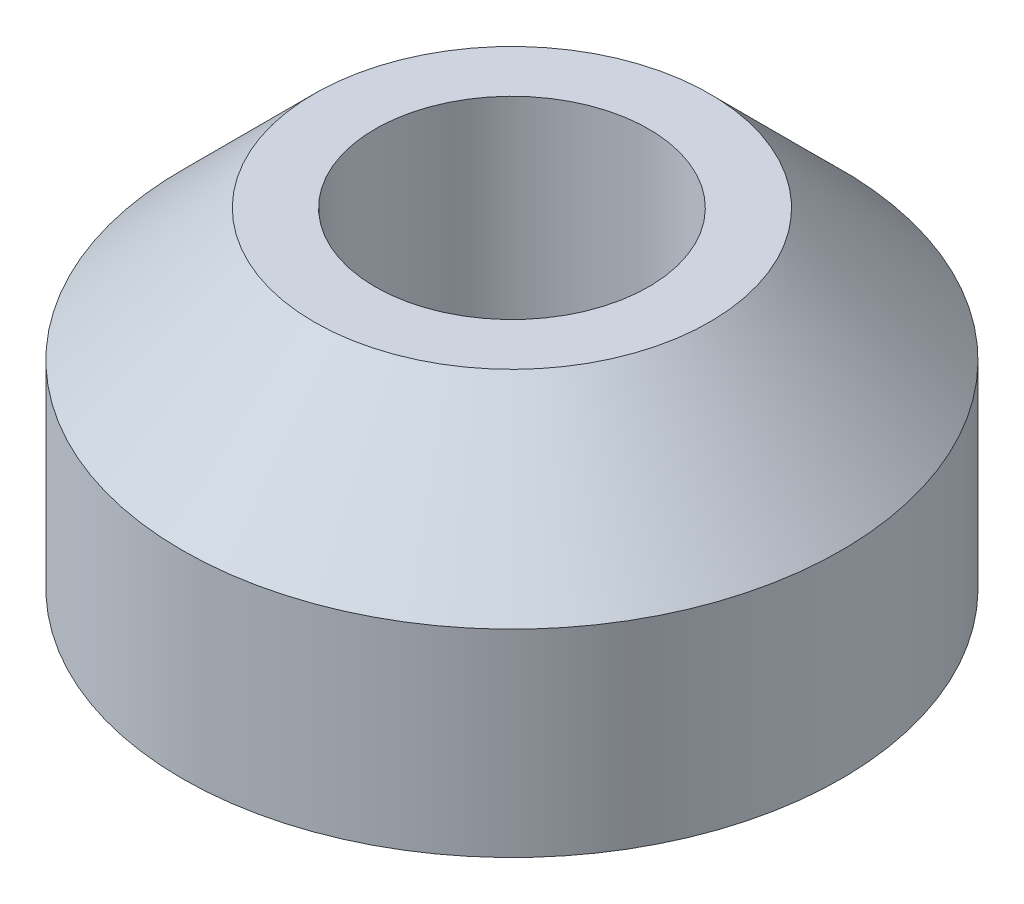
SolidWorks part; units mm, degrees
ref_plane "前视基准面" through (0, 0, 0) normal (0, 0, 1) x (1, 0, 0)
ref_plane "上视基准面" through (0, 0, 0) normal (0, 1, 0) x (1, 0, 0)
ref_plane "右视基准面" through (0, 0, 0) normal (1, 0, 0) x (0, 0, -1)
sketch "草图1" plane through (0, 0, 0) normal (0, 1, 0) x (1, 0, 0)
  circle A0 centre (0, 0) radius 4.15
  circle A1 centre (0, 0) radius 10
  dimension "D1" = 8.3
  dimension "D2" = 20
extrude "凸台-拉伸1" add sketch "草图1" along normal blind 10
chamfer "倒角1" distance 4 angle 45 1 edges at (0, 10, 10)
